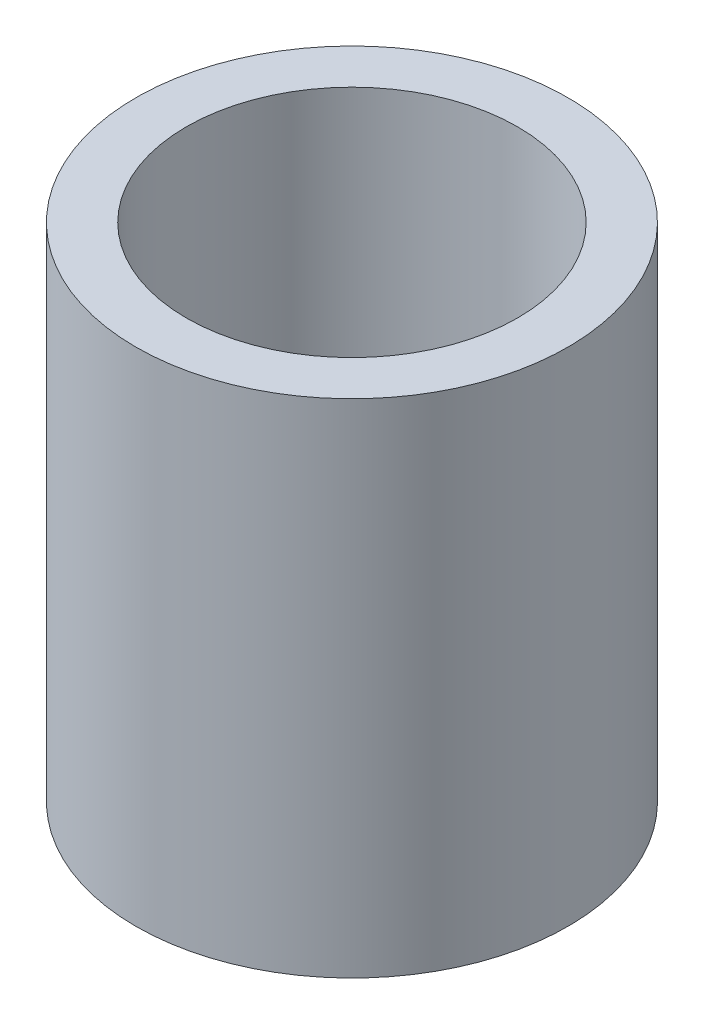
SolidWorks part; units mm, degrees
material "OMD-98"
ref_plane "Front Plane" through (0, 0, 0) normal (0, 0, 1) x (1, 0, 0)
ref_plane "Top Plane" through (0, 0, 0) normal (0, 1, 0) x (1, 0, 0)
ref_plane "Right Plane" through (0, 0, 0) normal (1, 0, 0) x (0, 0, -1)
sketch "Sketch1" plane through (0, 0, 0) normal (0, 1, 0) x (1, 0, 0)
  circle A0 centre (0, 0) radius 6.9
  circle A1 centre (0, 0) radius 9
  dimension "D1" = 18
  dimension "D2" = 13.8
extrude "Boss-Extrude1" add sketch "Sketch1" along normal blind 20.9
